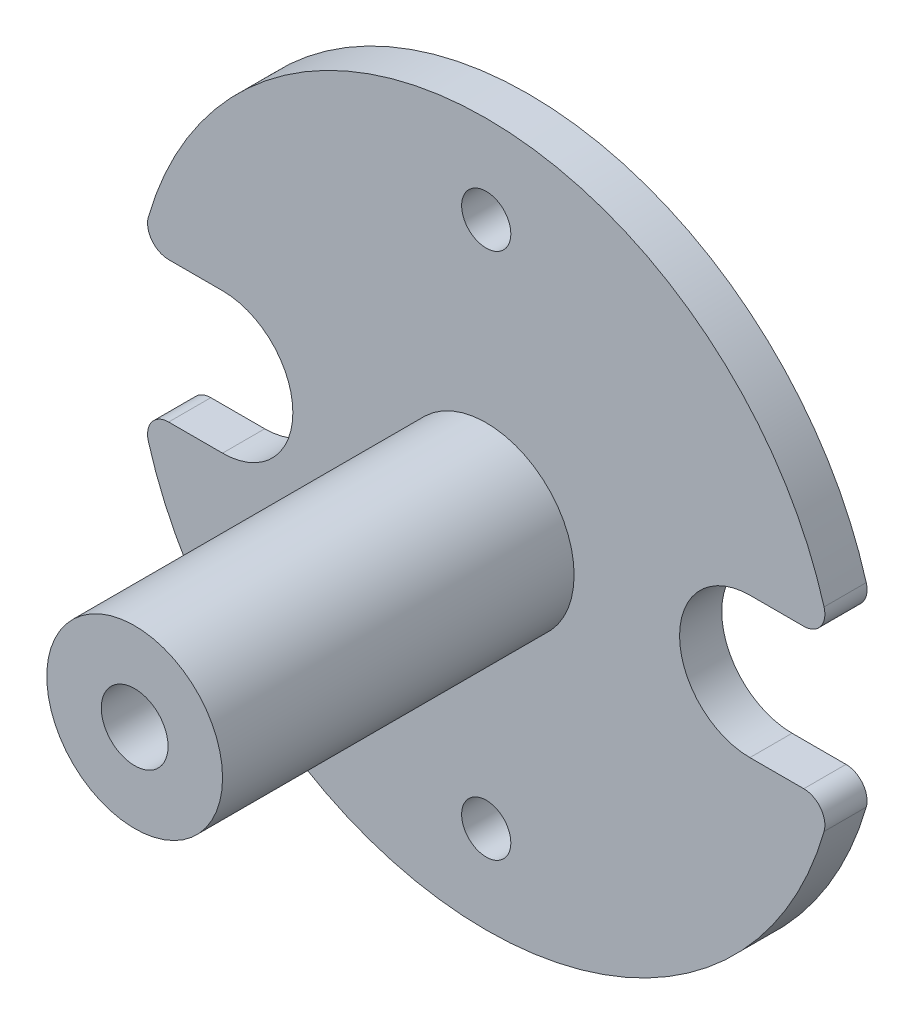
SolidWorks part; units mm, degrees
ref_plane "Front Plane" through (0, 0, 0) normal (0, 0, 1) x (1, 0, 0)
ref_plane "Top Plane" through (0, 0, 0) normal (0, 1, 0) x (1, 0, 0)
ref_plane "Right Plane" through (0, 0, 0) normal (1, 0, 0) x (0, 0, -1)
sketch "Sketch1" plane through (0, 0, 0) normal (0, 1, 0) x (1, 0, 0)
  line L0 (2.7016, 33.5049) -> (2.7016, 30.4569)
  line L1 (2.7016, 30.4569) -> (-16.3484, 30.4569)
  line L2 (-16.3484, 30.4569) -> (-16.3484, 5.0569)
  line L3 (-16.3484, 5.0569) -> (-22.6984, 5.0569)
  line L4 (-22.6984, 5.0569) -> (-22.6984, 33.5049)
  line L5 (-22.6984, 33.5049) -> (2.7016, 33.5049)
  dimension "D1" = 3.048
  dimension "D2" = 25.4
  dimension "D3" = 6.35
  dimension "D4" = 25.4
revolve "Revolve1" add sketch "Sketch1" angle 360 about L4
sketch "Sketch2" plane through (0, 0, -33.5049) normal (0, 0, -1) x (-1, 0, 0)
  line L0 (41.7484, -5.08) -> (47.5852, -5.08)
  line L1 (41.7484, 5.08) -> (47.5852, 5.08)
  line L2 (3.6484, 5.08) -> (-2.1885, 5.08)
  line L3 (3.6484, -5.08) -> (-2.1885, -5.08)
  circle A0 centre (22.6984, 0) radius 19.05 construction
  circle A1 centre (22.6984, -19.05) radius 1.778
  circle A2 centre (22.6984, 19.05) radius 1.778
  arc A3 (41.7484, 5.08) -> (41.7484, -5.08) centre (41.7484, 0) ccw
  circle A5 centre (22.6984, 0) radius 25.4 construction
  arc A6 (47.5852, -5.08) -> (47.5852, 5.08) centre (22.6984, 0) ccw
  arc A7 (3.6484, -5.08) -> (3.6484, 5.08) centre (3.6484, 0) ccw
  arc A8 (-2.1885, 5.08) -> (-2.1885, -5.08) centre (22.6984, 0) ccw
  point P16 (0, 0)
  point P22 (22.6984, 0)
  dimension "D1" = 38.1
  dimension "D2" = 3.556
  dimension "D3" = 3.556
  dimension "D4" = 10.16
  dimension "D5" = 2
extrude "Cut-Extrude2" cut sketch "Sketch2" against normal blind 5.08 contours A3 L0 A6 L1 | A7 L2 A8 L3 | A1 | A2
sketch "Sketch4" plane through (0, 0, -5.0569) normal (0, 0, 1) x (1, 0, 0)
  circle A0 centre (-22.6984, 0) radius 2.413
  dimension "D1" = 4.826
extrude "Cut-Extrude3" cut sketch "Sketch4" against normal blind 19.05
fillet "Fillet1" radius 1.524 4 edges at (2.1885, 5.08, -31.9809) (2.1885, -5.08, -31.9809) (-47.5852, 5.08, -31.9809) (-47.5852, -5.08, -31.9809)
